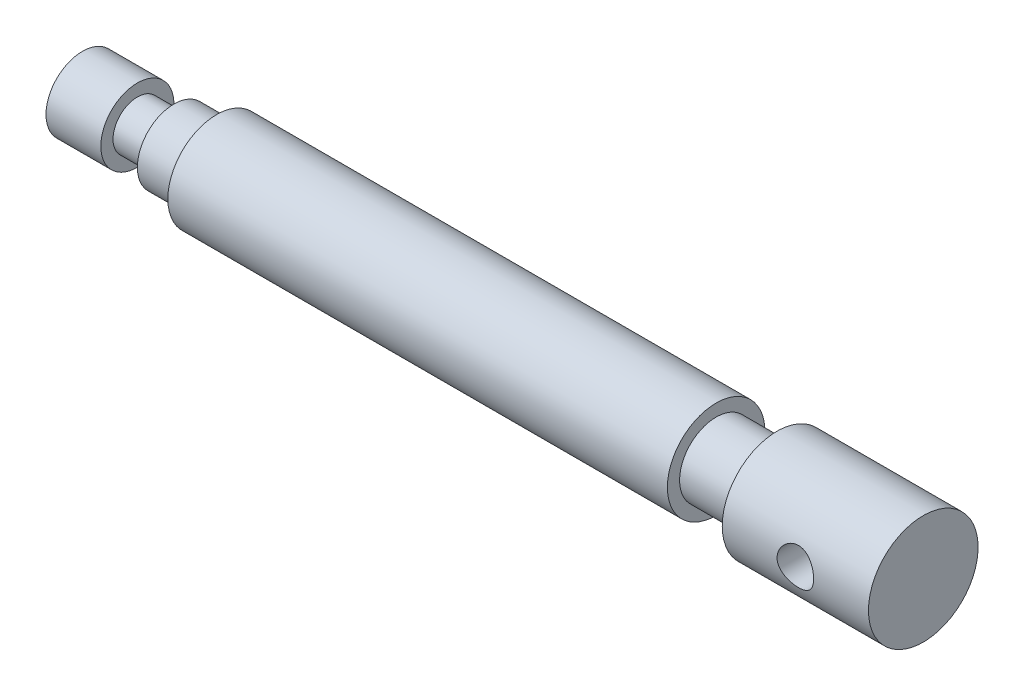
SolidWorks part; units mm, degrees
ref_plane "Front Plane" through (0, 0, 0) normal (0, 0, 1) x (1, 0, 0)
ref_plane "Top Plane" through (0, 0, 0) normal (0, 1, 0) x (1, 0, 0)
ref_plane "Right Plane" through (0, 0, 0) normal (1, 0, 0) x (0, 0, -1)
sketch "Sketch1" plane through (0, 0, 0) normal (0, 0, 1) x (1, 0, 0)
  line L0 (-69, 0) -> (69, 0) construction
  line L1 (69, 0) -> (69, 9)
  line L2 (69, 9) -> (45, 9)
  line L3 (45, 9) -> (45, 6)
  line L4 (45, 6) -> (35, 6)
  line L5 (35, 6) -> (35, 8)
  line L6 (35, 8) -> (-47, 8)
  line L7 (-69, 0) -> (-69, 6)
  line L8 (-69, 6) -> (-60, 6)
  line L9 (-60, 6) -> (-60, 4)
  line L10 (-60, 4) -> (-54, 4)
  line L11 (-54, 4) -> (-54, 6)
  line L12 (-54, 6) -> (-47, 6)
  line L13 (-47, 6) -> (-47, 8)
  line L14 (69, 0) -> (-69, 0)
  point P4 (0, 0)
  dimension "D1" = 138
  dimension "D2" = 18
  dimension "D3" = 24
  dimension "D4" = 82
  dimension "D5" = 12
  dimension "D6" = 9
  dimension "D7" = 8
  dimension "D8" = 6
  dimension "D9" = 10
  dimension "D10" = 16
revolve "Revolve1" add sketch "Sketch1" angle 360 about L0
sketch "Sketch2" plane through (0, 0, 0) normal (0, 0, 1) x (1, 0, 0)
  line L0 (57, 9) -> (57, 0) construction
  line L1 (69, 9) -> (45, 9) construction
  line L2 (57, 0) -> (69, 0) construction
  line L3 (69, -9) -> (69, 9) construction
  circle A0 centre (57, 0) radius 3
  dimension "D1" = 6
extrude "Cut-Extrude1" cut sketch "Sketch2" against normal through all both and the other way through all
